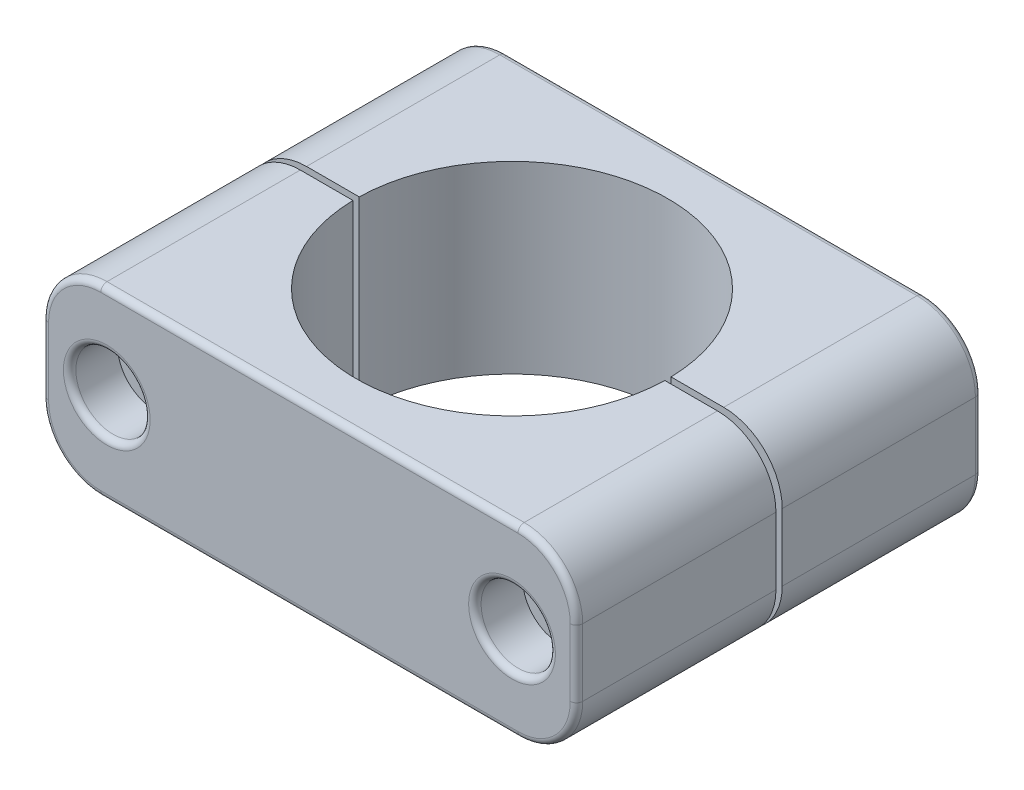
SolidWorks part; units mm, degrees
ref_plane "Front Plane" through (0, 0, 0) normal (0, 0, 1) x (1, 0, 0)
ref_plane "Top Plane" through (0, 0, 0) normal (0, 1, 0) x (1, 0, 0)
ref_plane "Right Plane" through (0, 0, 0) normal (1, 0, 0) x (0, 0, -1)
sketch "Sketch1" plane through (0, 0, 0) normal (0, 1, 0) x (1, 0, 0)
  line L1 (-43.5, -33) -> (43.5, -33)
  line L2 (-43.5, -33) -> (-43.5, 33)
  line L3 (-43.5, 33) -> (43.5, 33)
  line L4 (43.5, -33) -> (43.5, 33)
  circle A0 centre (0, 0) radius 25.4
  point P4 (43.5, 0)
  point P5 (0, 33)
  dimension "D3" = 50.8
  dimension "D1" = 66
  dimension "D2" = 87
extrude "Extrude1" add sketch "Sketch1" along normal mid plane 30
ref_plane "Plane1" through (33, 0, 0) normal (1, 0, 0) x (0, 0, -1)
sketch "Sketch4" plane through (33, 0, 0) normal (1, 0, 0) x (0, 0, -1)
  line L0 (-40.8, 0) -> (40.8, 0)
  line L1 (40.8, 0) -> (40.8, 6.05)
  line L2 (40.8, 6.05) -> (25.2, 6.05)
  line L3 (25.2, 6.05) -> (25.2, 3.302)
  line L4 (25.2, 3.302) -> (-25.2, 3.302)
  line L5 (-25.2, 3.302) -> (-25.2, 6.05)
  line L6 (-25.2, 6.05) -> (-40.8, 6.05)
  line L7 (-40.8, 6.05) -> (-40.8, 0)
  line L8 (40.8, 0) -> (55.5249, 0) construction
  line L9 (33, 15) -> (33, -15) construction
  line L10 (-33, 15) -> (-33, -15) construction
  point P2 (33, 6.05)
  point P13 (-33, 6.05)
  dimension "D1" = 6.604
  dimension "D2" = 12.1
  dimension "D3" = 7.8
revolve "Cut-Revolve1" cut sketch "Sketch4" angle 360 about L8
mirror "Mirror1" about plane through (0, 0, 0) normal (1, 0, 0) of "Cut-Revolve1"
fillet "Fillet1" radius 9.525 4 edges at (-43.5, -15, 0) (-43.5, 15, 0) (43.5, -15, 0) (43.5, 15, 0)
fillet "Fillet2" radius 1.016 20 edges at (-26.95, 0, -33) (40.7102, -12.2102, -33) (43.5, 0, -33) (40.7102, 12.2102, -33) (0, 15, -33) (-40.7102, 12.2102, -33) (-43.5, 0, -33) (-40.7102, -12.2102, -33) (0, -15, -33) (39.05, 0, -33) (-39.05, 0, 33) (-40.7102, 12.2102, 33) (0, 15, 33) (40.7102, 12.2102, 33) (43.5, 0, 33) (40.7102, -12.2102, 33) (0, -15, 33) (-40.7102, -12.2102, 33) (-43.5, 0, 33) (26.95, 0, 33)
sketch "Sketch3" plane through (0, 0, 0) normal (0, 1, 0) x (-1, 0, 0)
  line L3 (46.1872, -0.508) -> (-47.817, -0.508)
  line L4 (46.1872, 0.508) -> (-47.817, 0.508)
  line L5 (46.1872, -0.508) -> (46.1872, 0.508)
  line L6 (-47.817, -0.508) -> (-47.817, 0.508)
  point P0 (46.1872, 0)
  dimension "D1" = 1.016
extrude "Cut-Extrude1" cut sketch "Sketch3" against normal mid plane 50.8
